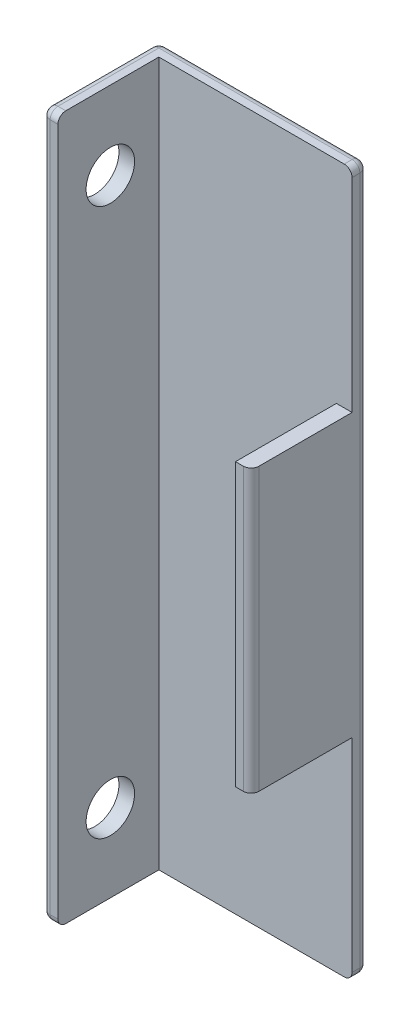
SolidWorks part; units mm, degrees
ref_plane "Front Plane" through (0, 0, 0) normal (0, 0, 1) x (1, 0, 0)
ref_plane "Top Plane" through (0, 0, 0) normal (0, 1, 0) x (1, 0, 0)
ref_plane "Right Plane" through (0, 0, 0) normal (1, 0, 0) x (0, 0, -1)
sketch "Sketch1" plane through (0, 0, 0) normal (0, 0, 1) x (1, 0, 0)
  line L1 (0, 0) -> (26.7, 0)
  line L2 (0, 0) -> (0, 90)
  line L3 (0, 90) -> (26.7, 90)
  line L4 (26.7, 0) -> (26.7, 90)
  dimension "D1" = 90
  dimension "D2" = 26.7
extrude "Boss-Extrude1" add sketch "Sketch1" along normal blind 2
sketch "Sketch2" plane through (0, 0, 2) normal (0, 0, 1) x (1, 0, 0)
  line L0 (0, 0) -> (26.7, 0) construction
  line L1 (0, 90) -> (2, 90)
  line L2 (0, 90) -> (0, 0)
  line L3 (0, 0) -> (2, 0)
  line L4 (2, 90) -> (2, 0)
  line L6 (26.7, 90) -> (24.7, 90)
  line L7 (26.7, 90) -> (26.7, 0)
  line L8 (26.7, 0) -> (24.7, 0)
  line L9 (24.7, 90) -> (24.7, 0)
  dimension "D1" = 2
extrude "Boss-Extrude2" add sketch "Sketch2" along normal blind 12.9
sketch "Sketch3" plane through (0, 0, 0) normal (-1, 0, 0) x (0, 0, 1)
  line L1 (2, 0) -> (2, 90) construction
  line L3 (14.9, 0) -> (0, 0) construction
  circle A0 centre (8.2, 10) radius 3.1
  dimension "D1" = 6.2
  dimension "D2" = 6.2
  dimension "D3" = 10
extrude "Cut-Extrude1" cut sketch "Sketch3" against normal through all
ref_plane "Plane1" through (0, 45, 0) normal (0, 1, 0) x (1, 0, 0)
mirror "Mirror1" about plane through (0, 45, 0) normal (0, 1, 0) of "Cut-Extrude1"
fillet "Fillet1" radius 1 1 edges at (13.35, 90, 0)
fillet "Fillet2" radius 1 3 edges at (0, 44.5, 0) (0, 89.7071, 0.2929) (0, 90, 7.95)
fillet "Fillet3" radius 1 3 edges at (26.7, 44.5, 0) (26.7, 89.7071, 0.2929) (26.7, 90, 7.95)
fillet "Fillet6" radius 1 5 edges at (13.35, 0, 0) (0.2929, 0, 0.2929) (26.7, 0, 7.95) (0, 0, 7.95) (26.4071, 0, 0.2929)
fillet "Fillet7" radius 1 5 edges at (1.5, 90, 14.9) (0, 45, 14.9) (0.2929, 89.7071, 14.9) (1.5, 0, 14.9) (0.2929, 0.2929, 14.9)
fillet "Fillet8" radius 1 5 edges at (25.2, 0, 14.9) (25.2, 90, 14.9) (26.4071, 89.7071, 14.9) (26.7, 45, 14.9) (26.4071, 0.2929, 14.9)
sketch "Sketch5" plane through (24.7, 0, 0) normal (-1, 0, 0) x (0, 0, 1)
  line L0 (14.9, 89) -> (14.9, 1) construction
  line L1 (2, 90) -> (14.9, 90)
  line L2 (2, 90) -> (2, 63)
  line L3 (2, 63) -> (14.9, 63)
  line L4 (14.9, 90) -> (14.9, 63)
  line L6 (2, 0) -> (14.9, 0)
  line L7 (2, 0) -> (2, 27)
  line L8 (2, 27) -> (14.9, 27)
  line L9 (14.9, 0) -> (14.9, 27)
  dimension "D1" = 27
  dimension "D2" = 27
extrude "Cut-Extrude2" cut sketch "Sketch5" against normal up to surface (2 mm away) contours L2 L1 L4 L3 | L7 L6 L9 L8 up to face at (26.7, 80, 11.3)
